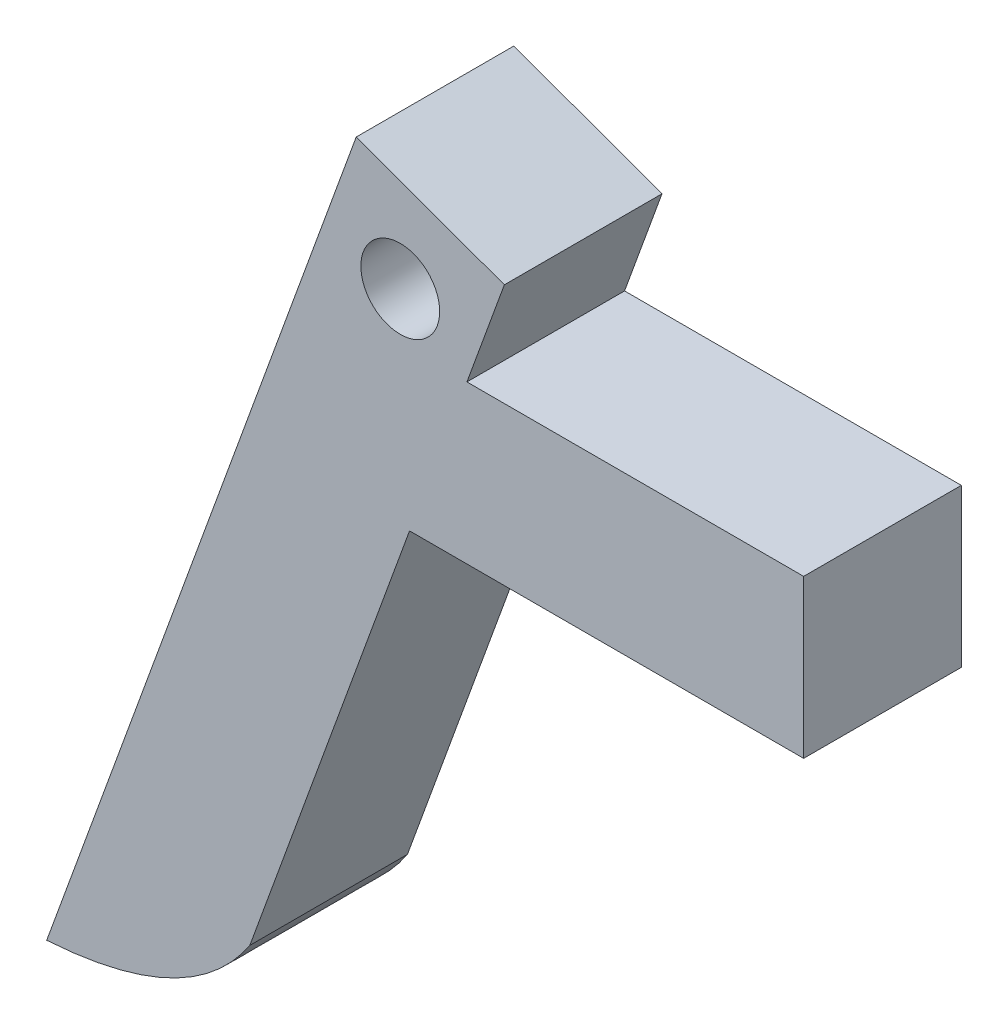
SolidWorks part; units mm, degrees
ref_plane "Front Plane" through (0, 0, 0) normal (0, 0, 1) x (1, 0, 0)
ref_plane "Top Plane" through (0, 0, 0) normal (0, 1, 0) x (1, 0, 0)
ref_plane "Right Plane" through (0, 0, 0) normal (1, 0, 0) x (0, 0, -1)
sketch "Sketch8" plane through (0, 0, 0) normal (0, 0, 1) x (1, 0, 0)
  line L0 (-13.8068, 18.2336) -> (-22.3782, -5.3161) construction
  line L1 (-73.2829, 0) -> (69.1112, 0) construction
  line L2 (9.8776, 0) -> (9.8776, 10)
  line L3 (9.8776, 10) -> (-11.4827, 10)
  line L4 (-11.4827, 10) -> (-9.1083, 16.5235)
  line L6 (-18.5053, 19.9437) -> (-38.1392, -34)
  line L8 (-25.2553, -27.84) -> (-15.1224, 0)
  line L9 (-15.1224, 0) -> (9.8776, 0)
  line L10 (-18.5053, 19.9437) -> (-9.1083, 16.5235)
  circle A0 centre (-15.7117, 13) radius 2.5
  spline S0 degree 2 poles (-38.1392, -34) (-28.9526, -33.4107) (-25.2553, -27.84) knots 0 0 0 0.686191 0.686191 0.686191
  dimension "D2" = 3
  dimension "D7" = 110
  dimension "D1" = 10
  dimension "D3" = 10
  dimension "D4" = 10
  dimension "D6" = 25
extrude "Boss-Extrude4" add sketch "Sketch8" along normal blind 10 contours A0 | L3 L4 L10 L6 S0 L8 L9 L2
